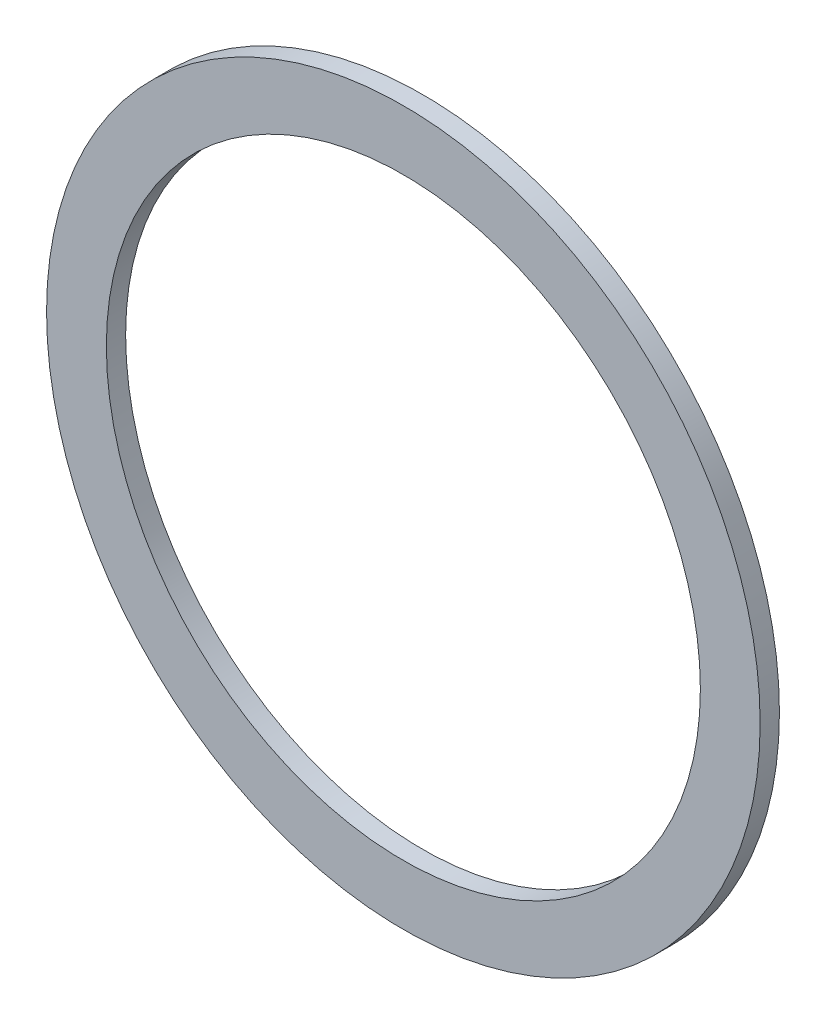
SolidWorks part; units mm, degrees
ref_plane "Спереди" through (0, 0, 0) normal (0, 0, 1) x (1, 0, 0)
ref_plane "Сверху" through (0, 0, 0) normal (0, 1, 0) x (1, 0, 0)
ref_plane "Справа" through (0, 0, 0) normal (1, 0, 0) x (0, 0, -1)
sketch "Эскиз1" plane through (0, 0, 0) normal (0, 0, 1) x (1, 0, 0)
  circle A0 centre (0, 0) radius 18.5
  circle A1 centre (0, 0) radius 15.4
extrude "Circlip_envelope" add sketch "Эскиз1" along normal blind 1 from offset 21.5
